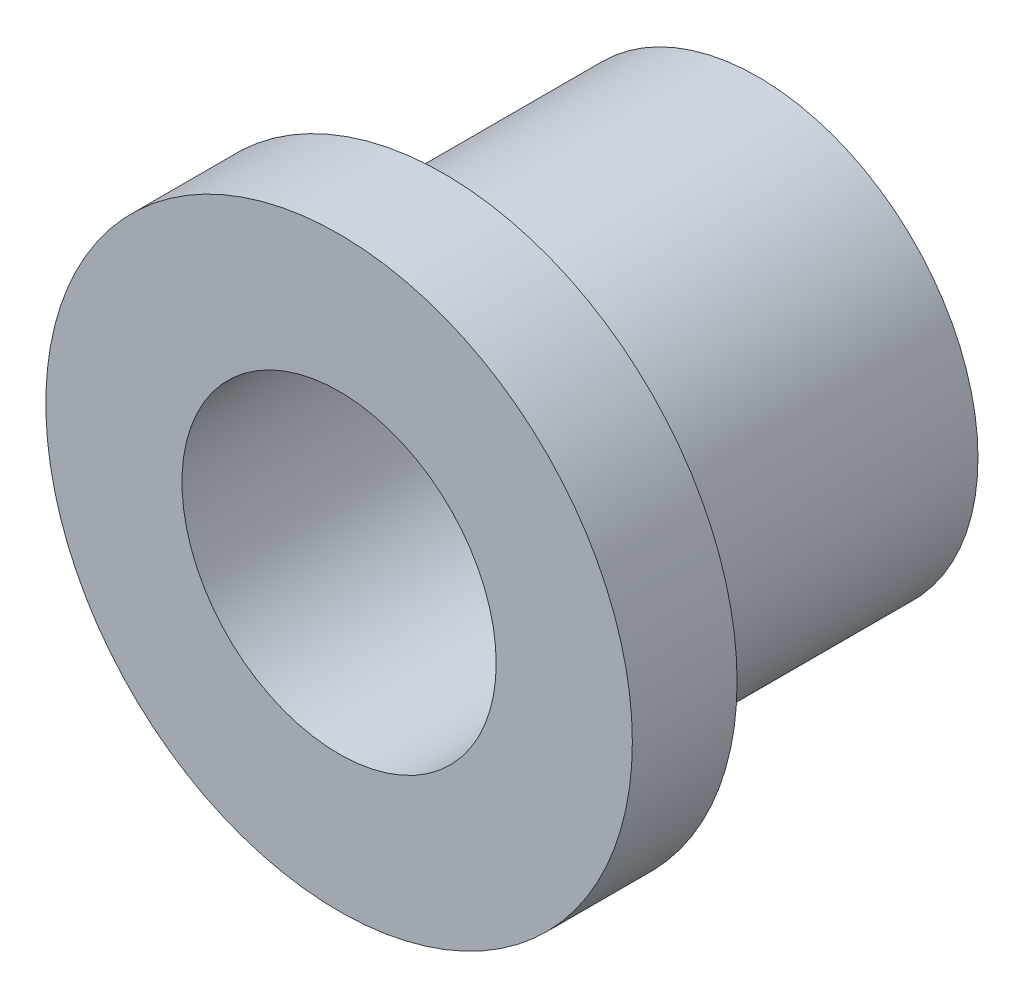
SolidWorks part; units mm, degrees
ref_plane "Front Plane" through (0, 0, 0) normal (0, 0, 1) x (1, 0, 0)
ref_plane "Top Plane" through (0, 0, 0) normal (0, 1, 0) x (1, 0, 0)
ref_plane "Right Plane" through (0, 0, 0) normal (1, 0, 0) x (0, 0, -1)
sketch "Sketch1" plane through (0, 0, 0) normal (0, 0, 1) x (1, 0, 0)
  circle A0 centre (0, 0) radius 7.5
  circle A1 centre (0, 0) radius 10.5
  dimension "D1" = 15
  dimension "D2" = 21
extrude "Boss-Extrude1" add sketch "Sketch1" along normal blind 15
sketch "Sketch2" plane through (0, 0, 15) normal (0, 0, 1) x (1, 0, 0)
  circle A0 centre (0, 0) radius 7.5
  circle A1 centre (0, 0) radius 14
  dimension "D1" = 15
  dimension "D2" = 28
extrude "Boss-Extrude2" add sketch "Sketch2" along normal blind 5
